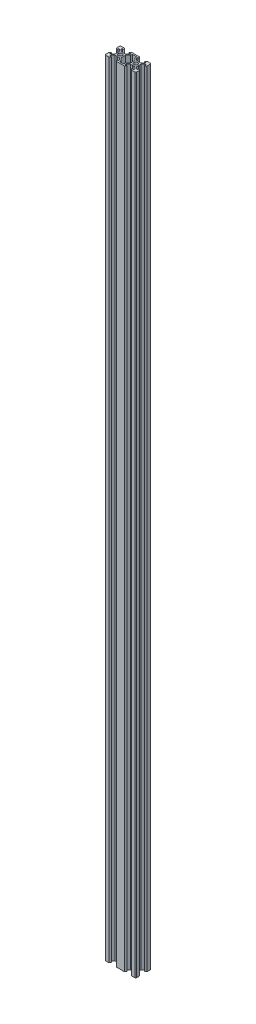
SolidWorks part; units mm, degrees
material "6063-T5"
material "6063-T5"
ref_plane "Plano frontal" through (0, 0, 0) normal (0, 0, 1) x (1, 0, 0)
ref_plane "Plano superior" through (0, 0, 0) normal (0, 1, 0) x (1, 0, 0)
ref_plane "Plano direito" through (0, 0, 0) normal (1, 0, 0) x (0, 0, -1)
sketch "Esboço1" plane through (0, 0, 0) normal (0, 0, 1) x (1, 0, 0)
  line L0 (0, 0) -> (0, 1015)
  dimension "D1" = 1015
other "Retangular PF20-12 - PERFIL 2040 V-SLOT(1)"
ref_plane "Plano1" through (0, 0, 0) normal (0, 1, 0) x (-1, 0, 0)
sketch "Sketch13" plane through (0, 0, 0) normal (0, 1, 0) x (-1, 0, 0)
  line L0 (-14.8, 10) -> (-13, 8.2)
  line L1 (-13, 8.2) -> (-15.5, 8.2)
  line L2 (-15.5, 8.2) -> (-15.5, 6.5607)
  line L3 (-15.5, 6.5607) -> (-12.9393, 4)
  line L4 (-12.9393, 4) -> (-10.3, 4)
  line L5 (-4.5, 6.5607) -> (-7.0607, 4)
  line L6 (-4.5, 8.2) -> (-4.5, 6.5607)
  line L7 (-7, 8.2) -> (-4.5, 8.2)
  line L8 (-5.2, 10) -> (-7, 8.2)
  line L9 (-10.3, 4) -> (-10, 3.7)
  line L10 (-9.7, 4) -> (-10, 3.7)
  line L11 (-9.7, 4) -> (-7.0607, 4)
  line L12 (-2.7, 8.2) -> (-2.7, 6.2393)
  line L13 (-2.7, 6.2393) -> (-6, 2.9393)
  line L14 (-2.7, 8.2) -> (2.7, 8.2)
  line L15 (2.7, 6.2393) -> (6, 2.9393)
  line L16 (2.7, 8.2) -> (2.7, 6.2393)
  line L17 (-5.2, -10) -> (5.2, -10)
  line L18 (-5.2, -10) -> (-7, -8.2)
  line L19 (-7, -8.2) -> (-4.5, -8.2)
  line L20 (-4.5, -8.2) -> (-4.5, -6.5607)
  line L21 (-4.5, -6.5607) -> (-7.0607, -4)
  line L22 (-7.0607, -4) -> (-9.7, -4)
  line L23 (-9.7, -4) -> (-10, -3.7)
  line L24 (-10.3, -4) -> (-10, -3.7)
  line L25 (-10.3, -4) -> (-12.9393, -4)
  line L26 (-15.5, -6.5607) -> (-12.9393, -4)
  line L27 (-15.5, -8.2) -> (-15.5, -6.5607)
  line L28 (-13, -8.2) -> (-15.5, -8.2)
  line L29 (-14.8, -10) -> (-13, -8.2)
  line L30 (-20, -4.8) -> (-20, -9)
  line L31 (-20, -4.8) -> (-18.2, -3)
  line L32 (-18.2, -3) -> (-18.2, -5.5)
  line L33 (-18.2, -5.5) -> (-16.5607, -5.5)
  line L34 (-16.5607, -5.5) -> (-14, -2.9393)
  line L35 (-14, -2.9393) -> (-14, -0.3)
  line L36 (-14, -0.3) -> (-13.7, 0)
  line L37 (-14, 0.3) -> (-13.7, 0)
  line L38 (-14, 0.3) -> (-14, 2.9393)
  line L39 (-16.5607, 5.5) -> (-14, 2.9393)
  line L40 (-18.2, 5.5) -> (-16.5607, 5.5)
  line L41 (-18.2, 3) -> (-18.2, 5.5)
  line L42 (-20, 4.8) -> (-18.2, 3)
  line L43 (-14.8, 10) -> (-19, 10)
  line L56 (5.2, 10) -> (-5.2, 10)
  line L57 (5.2, 10) -> (7, 8.2)
  line L58 (7, 8.2) -> (4.5, 8.2)
  line L59 (4.5, 8.2) -> (4.5, 6.5607)
  line L60 (4.5, 6.5607) -> (7.0607, 4)
  line L61 (9.7, 4) -> (7.0607, 4)
  line L62 (9.7, 4) -> (10, 3.7)
  line L63 (10.3, 4) -> (10, 3.7)
  line L64 (12.9393, 4) -> (10.3, 4)
  line L65 (15.5, 6.5607) -> (12.9393, 4)
  line L66 (15.5, 8.2) -> (15.5, 6.5607)
  line L67 (13, 8.2) -> (15.5, 8.2)
  line L68 (14.8, 10) -> (13, 8.2)
  line L69 (20, 4.8) -> (18.2, 3)
  line L70 (18.2, 3) -> (18.2, 5.5)
  line L71 (18.2, 5.5) -> (16.5607, 5.5)
  line L72 (16.5607, 5.5) -> (14, 2.9393)
  line L73 (14, 0.3) -> (14, 2.9393)
  line L74 (14, 0.3) -> (13.7, 0)
  line L75 (14, -0.3) -> (13.7, 0)
  line L76 (14, -2.9393) -> (14, -0.3)
  line L77 (16.5607, -5.5) -> (14, -2.9393)
  line L78 (18.2, -5.5) -> (16.5607, -5.5)
  line L79 (18.2, -3) -> (18.2, -5.5)
  line L80 (20, -4.8) -> (18.2, -3)
  line L81 (20, -9) -> (20, -4.8)
  line L82 (14.8, -10) -> (13, -8.2)
  line L83 (13, -8.2) -> (15.5, -8.2)
  line L84 (15.5, -8.2) -> (15.5, -6.5607)
  line L85 (15.5, -6.5607) -> (12.9393, -4)
  line L86 (10.3, -4) -> (12.9393, -4)
  line L87 (10.3, -4) -> (10, -3.7)
  line L88 (9.7, -4) -> (10, -3.7)
  line L89 (7.0607, -4) -> (9.7, -4)
  line L90 (4.5, -6.5607) -> (7.0607, -4)
  line L91 (4.5, -8.2) -> (4.5, -6.5607)
  line L92 (7, -8.2) -> (4.5, -8.2)
  line L93 (5.2, -10) -> (7, -8.2)
  line L99 (-6, 2.9393) -> (-6, -2.9393)
  line L100 (-2.7, -6.2393) -> (-6, -2.9393)
  line L101 (-2.7, -8.2) -> (-2.7, -6.2393)
  line L102 (-2.7, -8.2) -> (2.7, -8.2)
  line L103 (2.7, -8.2) -> (2.7, -6.2393)
  line L104 (2.7, -6.2393) -> (6, -2.9393)
  line L105 (6, 2.9393) -> (6, -2.9393)
  line L106 (-20, 9) -> (-20, 4.8)
  line L107 (-19, -10) -> (-14.8, -10)
  line L108 (19, 10) -> (14.8, 10)
  line L109 (20, 4.8) -> (20, 9)
  line L110 (14.8, -10) -> (19, -10)
  arc A3 (-20, -9) -> (-19, -10) centre (-19, -9) ccw
  arc A4 (-19, 10) -> (-20, 9) centre (-19, 9) ccw
  arc A5 (20, 9) -> (19, 10) centre (19, 9) ccw
  arc A6 (19, -10) -> (20, -9) centre (19, -9) ccw
  circle A7 centre (-10, 0) radius 2.5
  circle A8 centre (10, 0) radius 2.5
  point P1 (-20, 10)
  point P2 (20, 10)
  point P4 (20, 0)
  point P108 (0, 10)
  point P109 (0, 0)
  point P111 (20, -10)
  point P112 (10, -10)
  point P113 (-10, -10)
  point P114 (-20, -10)
  point P115 (-20, 0)
  point P116 (-10, 10)
  point P117 (10, 10)
  point P118 (-10, 0)
  point P119 (10, 0)
  point P120 (0, -10)
  point P121 (0, 0)
